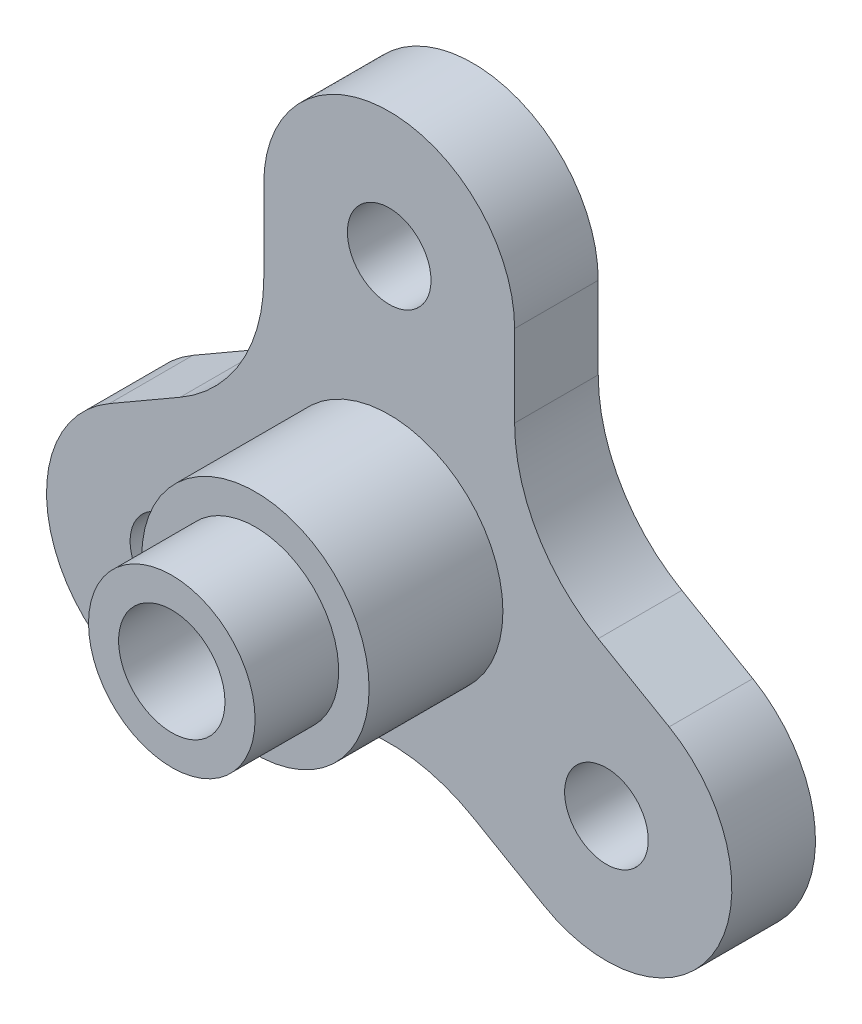
SolidWorks part; units mm, degrees
material "6061-T6 (SS)"
ref_plane "Front Plane" through (0, 0, 0) normal (0, 0, 1) x (1, 0, 0)
ref_plane "Top Plane" through (0, 0, 0) normal (0, 1, 0) x (1, 0, 0)
ref_plane "Right Plane" through (0, 0, 0) normal (1, 0, 0) x (0, 0, -1)
sketch "Sketch1" plane through (0, 0, 0) normal (1, 0, 0) x (0, 0, -1)
  line L0 (0, 2.0193) -> (0, 4.318)
  line L1 (0, 4.318) -> (5.08, 4.318)
  line L3 (5.08, 4.318) -> (5.08, 15.875)
  line L4 (8.255, 15.875) -> (8.255, 2.0193)
  line L5 (0, 2.0193) -> (8.255, 2.0193)
  line L6 (5.08, 15.875) -> (8.255, 15.875)
  line L7 (0, 0) -> (10.5039, 0) construction
  dimension "D1" = 2.0193
  dimension "D2" = 4.318
  dimension "D3" = 5.08
  dimension "D4" = 3.175
  dimension "D5" = 15.875
revolve "Revolve1" add sketch "Sketch1" angle 360 about L7
hole_wizard "1/8 (0.1250) Dowel Hole1" positions "Sketch2" profile "Sketch3" hole size "1/8" standard "ANSI Inch" end condition through all
sketch "Sketch2" plane through (0, 0, -5.08) normal (0, 0, 1) x (1, 0, 0)
  point P0 (0, 9.525)
  point P9 (0, 0)
  dimension "D2" = 9.525
sketch "Sketch3" plane through (0, 9.525, -5.08) normal (1, 0, 0) x (0, -1, 0)
  line L0 (0, 0) -> (0, 3.175)
  line L1 (0, 3.175) -> (1.5875, 3.175)
  line L2 (1.5875, 3.175) -> (1.5875, 0)
  line L5 (1.5875, 0) -> (0, 0)
  line L11 (0, -6.35) -> (0, 107.95) construction
  dimension "Thru Hole Dia." = 3.175
  dimension "Thru Hole Depth" = 3.175
hole_wizard "#4-40 Tapped Hole1" [suppressed] positions "Sketch4" profile "Sketch6" tap size "#4-40" standard "ANSI Inch"
sketch "Sketch4" plane through (0, 0, 0) normal (0, 1, 0) x (1, 0, 0)
  point P0 (0, 3.175)
  dimension "D1" = 3.175
sketch "Sketch6" plane through (0, 0, -3.175) normal (1, 0, 0) x (0, 0, -1)
  line L0 (0, 0) -> (0, 12.7)
  line L1 (0, 12.7) -> (1.1303, 12.7)
  line L2 (1.1303, 12.7) -> (1.1303, 0)
  line L5 (1.1303, 0) -> (0, 0)
  line L11 (0, -6.35) -> (0, 107.95) construction
  dimension "Thru Tap Drill Dia." = 2.2606
  dimension "Thru Tap Drill Depth" = 12.7
cosmetic thread "Hole Thread2" [suppressed] parameters "D2"=2.8448
pattern_circular "CirPattern1" [suppressed] count 2 over 360
pattern_circular "CirPattern2" count 3 over 360 about axis through (0, 0, 0) along (0, 0, 1) of "1/8 (0.1250) Dowel Hole1"
sketch "Sketch7" plane through (0, 0, -5.08) normal (0, 0, 1) x (1, 0, 0)
  line L0 (4.7625, 9.525) -> (4.7625, 2.7496)
  line L1 (-4.7625, 9.525) -> (-4.7625, 2.7496)
  line L2 (10.6301, -0.6381) -> (4.7625, 2.7496)
  line L3 (-10.6301, -0.6381) -> (-4.7625, 2.7496)
  line L4 (5.8676, -8.8869) -> (0, -5.4993)
  line L5 (-5.8676, -8.8869) -> (0, -5.4993)
  circle A0 centre (-8.2489, -4.7625) radius 1.5875 construction
  circle A1 centre (8.2489, -4.7625) radius 1.5875 construction
  circle A2 centre (0, 9.525) radius 1.5875 construction
  circle A3 centre (-8.2489, -4.7625) radius 1.5875
  circle A4 centre (8.2489, -4.7625) radius 1.5875
  circle A5 centre (0, 9.525) radius 1.5875
  arc A6 (-4.7625, 9.525) -> (4.7625, 9.525) centre (0, 9.525) cw
  arc A7 (5.8676, -8.8869) -> (10.6301, -0.6381) centre (8.2489, -4.7625) ccw
  arc A8 (-5.8676, -8.8869) -> (-10.6301, -0.6381) centre (-8.2489, -4.7625) cw
  circle M5 centre (0, 0) radius 15.875
  dimension "D1" = 4.7625
  dimension "D2" = 4.7625
  dimension "D3" = 4.7625
  dimension "D4" = 120
  dimension "D5" = 120
extrude "Cut-Extrude1" cut sketch "Sketch7" against normal blind 10 contours A8 L3 L1 A6 M5 | A7 A6 L0 L2 M5 | L5 A8 A7 L4 M5
fillet "Fillet1" radius 6.35 3 edges at (-4.7625, 2.7496, -6.6675) (0, -5.4993, -6.6675) (4.7625, 2.7496, -6.6675)
sketch "Sketch11" plane through (0, 0, 0) normal (0, 0, 1) x (1, 0, 0)
  circle A0 centre (0, 0) radius 2.0193 construction
  circle A1 centre (0, 0) radius 2.0193
  circle A2 centre (0, 0) radius 3.1623
  dimension "D1" = 6.3246
extrude "Boss-Extrude1" add sketch "Sketch11" along normal blind 3.175
equation "\"D2@Sketch7\"=\"D1@Sketch7\""
equation "\"D3@Sketch7\"=\"D1@Sketch7\""
